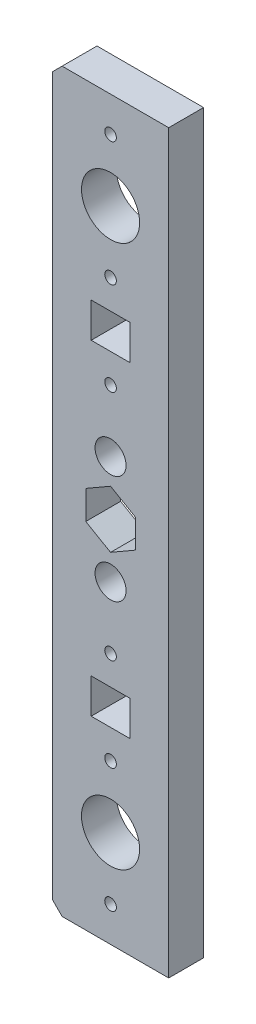
SolidWorks part; units mm, degrees
ref_plane "Front Plane" through (0, 0, 0) normal (0, 0, 1) x (1, 0, 0)
ref_plane "Top Plane" through (0, 0, 0) normal (0, 1, 0) x (1, 0, 0)
ref_plane "Right Plane" through (0, 0, 0) normal (1, 0, 0) x (0, 0, -1)
sketch "Model" plane through (0, 0, 0) normal (0, 0, 1) x (1, 0, 0)
  line L0 (-30, 185) -> (0, 185) construction
  line L1 (-27.5, 0) -> (0, 0)
  line L2 (-30, 2.5) -> (-30, 187.5)
  line L3 (-27.5, 190) -> (0, 190)
  line L4 (0, 0) -> (0, 190)
  line L5 (-30, 95) -> (0, 95) construction
  line L6 (-20, 141.5) -> (-10, 141.5)
  line L7 (-20, 141.5) -> (-20, 132.5)
  line L8 (-20, 132.5) -> (-10, 132.5)
  line L9 (-10, 141.5) -> (-10, 132.5)
  line L10 (-20, 141.5) -> (-10, 132.5) construction
  line L11 (-20, 132.5) -> (-10, 141.5) construction
  line L12 (-20, 57.5) -> (-10, 48.5) construction
  line L13 (-20, 48.5) -> (-10, 57.5) construction
  line L14 (-10, 48.5) -> (-10, 57.5)
  line L15 (-20, 57.5) -> (-10, 57.5)
  line L16 (-20, 48.5) -> (-20, 57.5)
  line L17 (-20, 48.5) -> (-10, 48.5)
  line L18 (-15, 165) -> (0, 165) construction
  line L19 (-27.5, 190) -> (-30, 187.5)
  line L20 (-15, 87.6099) -> (-8.6, 91.305)
  line L21 (-8.6, 91.305) -> (-8.6, 98.695)
  line L22 (-15, 185) -> (-15, 0) construction
  line L23 (-8.6, 98.695) -> (-15, 102.3901)
  line L24 (-15, 102.3901) -> (-21.4, 98.695)
  line L25 (-21.4, 98.695) -> (-21.4, 91.305)
  line L26 (-21.4, 91.305) -> (-15, 87.6099)
  line L27 (-30, 2.5) -> (-27.5, 0)
  line L28 (-15, 149) -> (32.8615, 149) construction
  line L29 (32.8615, 149) -> (32.8615, 125) construction
  line L30 (32.8615, 125) -> (-15, 125) construction
  line L31 (-15, 137) -> (32.8615, 137) construction
  circle A0 centre (-15, 165) radius 7.5
  circle A1 centre (-15, 95) radius 6.4 construction
  circle A4 centre (-15, 109) radius 4
  circle A5 centre (-15, 25) radius 7.5
  circle A6 centre (-15, 81) radius 4
  circle A7 centre (-15, 181) radius 1.5
  circle A8 centre (-15, 9) radius 1.5
  circle A9 centre (-15, 149) radius 1.5
  circle A10 centre (-15, 41) radius 1.5
  circle A11 centre (-15, 125) radius 1.5
  circle A12 centre (-15, 65) radius 1.5
  point P18 (-15, 137)
  point P29 (-15, 53)
  dimension "D7" = 8
  dimension "D11" = 15
  dimension "D14" = 3
  dimension "D10" = 9
  dimension "D12" = 10
  dimension "D2" = 5
  dimension "D5" = 30
  dimension "D6" = 190
  dimension "D15" = 16
  dimension "D3" = 12.8
  dimension "D9" = 14
  dimension "D16" = 70
  dimension "D4" = 2.5
  dimension "D17" = 135
  dimension "D8" = 30
extrude "Boss-Extrude1" add sketch "Model" along normal blind 9
equation "\"material-thickness\" = 9mm"
equation "\"tab-width-large\" = 30mm ' Width of the large version of the Tab"
equation "\"plate-supporttab-gapheight\" = 20mm"
equation "\"linear-bar-dia\" = 8mm ' Diameter of the metal slide bar used on the X Axis"
equation "\"linear-bar-bearingouter-dia\" = 15mm ' Diameter of the outer side of the bearing"
equation "\"linear-thread-dia\" = 8mm ' Diameter of the metal threaded rod used on the X Axis"
equation "\"linear-thread-nut-dia\" = 12.8mm ' Outer Diameter of the Nut used on the X Axis, typically M8 = 10mm"
equation "\"D10@Model\" = \"material-thickness\""
equation "\"D1@Boss-Extrude1\"= \"material-thickness\""
equation "\"D7@Model\"=\"linear-bar-dia\""
equation "\"D11@Model\"=\"linear-bar-bearingouter-dia\""
equation "\"D3@Model\"=\"linear-thread-nut-dia\""
